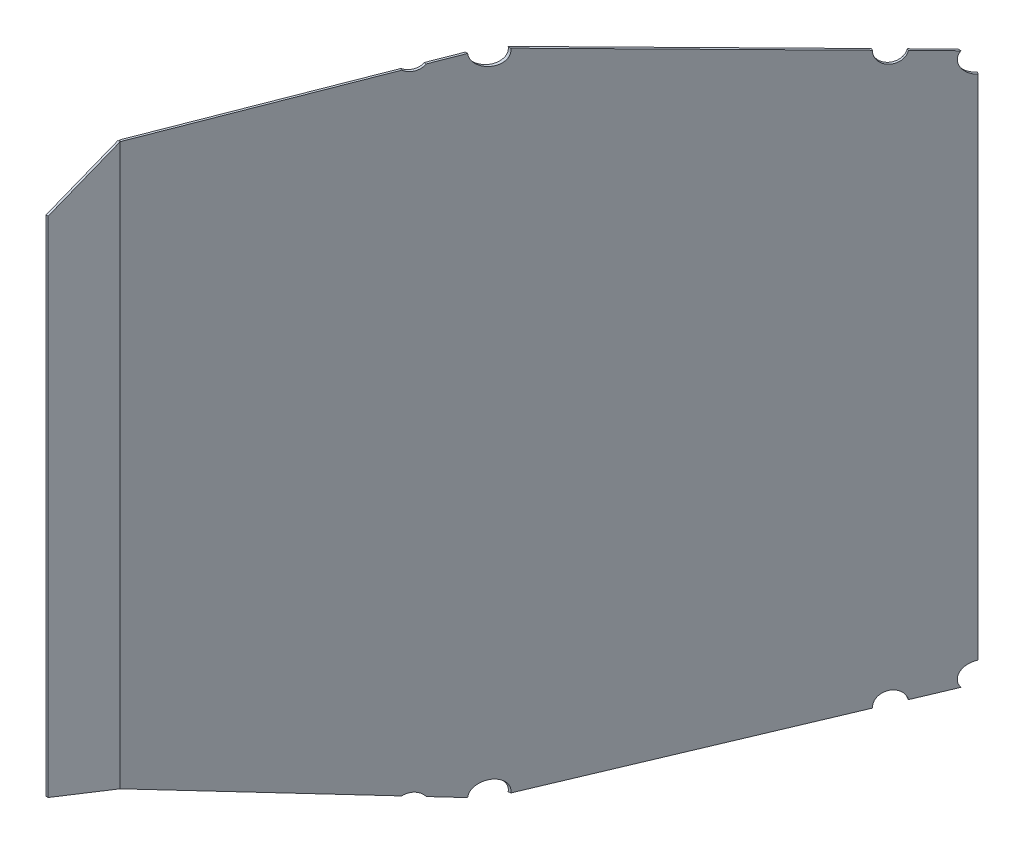
SolidWorks part; units mm, degrees
material "6061-T6 (SS)"
ref_plane "X-Y Datum" through (0, 0, 0) normal (0, 0, 1) x (1, 0, 0)
ref_plane "X-Z Datum" through (0, 0, 0) normal (0, 1, 0) x (1, 0, 0)
ref_plane "Y-Z Datum" through (0, 0, 0) normal (1, 0, 0) x (0, 0, -1)
ref_plane "Plane2" through (251.4767, 0, 168.3074) normal (-0.831, 0, -0.5562) x (-0.5562, 0, 0.831)
sketch "Sketch3" plane through (251.4767, 0, 168.3074) normal (-0.831, 0, -0.5562) x (-0.5562, 0, 0.831)
  line L0 (-187.2045, -273.05) -> (-187.2045, 273.05)
  line L1 (-187.2045, 273.05) -> (164.4025, 323.85)
  line L2 (429.2995, -279.4) -> (429.2995, 279.4)
  line L3 (429.2995, 279.4) -> (164.4025, 323.85)
  line L4 (-187.2045, 0) -> (429.2995, 0)
  line L5 (429.2995, -279.4) -> (164.4025, -323.85)
  line L6 (-187.2045, -273.05) -> (164.4025, -323.85)
  dimension "D1" = 273.05
  dimension "D2" = 279.4
  dimension "D3" = 323.85
extrude "Boss-Extrude1" add sketch "Sketch3" along normal blind 2.159 contours L0 L4 L2 L3 L1 | L0 L6 L5 L2 L4
ref_plane "Plane3" through (12.7, 0, 0) normal (-1, 0, 0) x (0, 0, 1)
sketch "Sketch4" plane through (12.7, 0, 0) normal (-1, 0, 0) x (0, 0, 1)
  line L0 (525.0759, -279.4) -> (525.0759, 279.4) construction
  line L1 (525.0759, -279.4) -> (525.0759, 279.4)
  line L3 (525.0759, 0) -> (596.9, 0)
  line L4 (525.0759, 279.4) -> (596.9, 251.0123)
  line L5 (596.9, 251.0123) -> (596.9, -251.0123)
  line L6 (525.0759, -279.4) -> (596.9, -251.0123)
extrude "Boss-Extrude2" add sketch "Sketch4" along normal blind 2.159 separate body contours L1 L6 L5 L3 | L5 L4 L1 L3
ref_plane "Plane4" through (825.5, 177.8, 47.625) normal (-0.9802, 0.1844, -0.0728) x (-0.0715, 0.0135, 0.9973)
sketch "Sketch5" plane through (825.5, 177.8, 47.625) normal (-0.9802, 0.1844, -0.0728) x (-0.0715, 0.0135, 0.9973)
  circle A0 centre (0, 0) radius 12.954
  dimension "D1" = 25.908
extrude "Cut-Extrude1" cut sketch "Sketch5" along normal blind 621.665
ref_plane "Plane5" through (825.5, 227.0125, 304.8) normal (-0.8987, 0.1001, -0.4271) x (-0.4245, 0.0473, 0.9042)
sketch "Sketch6" plane through (825.5, 227.0125, 304.8) normal (-0.8987, 0.1001, -0.4271) x (-0.4245, 0.0473, 0.9042)
  circle A0 centre (0, 0) radius 12.954
  dimension "D1" = 25.908
extrude "Cut-Extrude2" cut sketch "Sketch6" along normal through all
ref_plane "Plane6" through (825.5, 227.0125, 304.8) normal (-0.9902, 0.1398, -0.0002) x (-0.0002, 0, 1)
sketch "Sketch7" plane through (825.5, 227.0125, 304.8) normal (-0.9902, 0.1398, -0.0002) x (-0.0002, 0, 1)
  circle A0 centre (0, 0) radius 12.954
  dimension "D1" = 25.908
extrude "Cut-Extrude3" cut sketch "Sketch7" along normal through all
ref_plane "Plane7" through (825.5, 220.2924, 603.4647) normal (-0.9311, 0.1391, -0.3371) x (-0.3334, 0.0498, 0.9415)
sketch "Sketch8" plane through (825.5, 220.2924, 603.4647) normal (-0.9311, 0.1391, -0.3371) x (-0.3334, 0.0498, 0.9415)
  circle A0 centre (0, 0) radius 12.954
  dimension "D1" = 25.908
extrude "Cut-Extrude4" cut sketch "Sketch8" along normal through all
mirror "Mirror1" about plane through (0, 0, 0) normal (0, 1, 0) of "Cut-Extrude4", "Cut-Extrude3", "Cut-Extrude2", "Cut-Extrude1"
